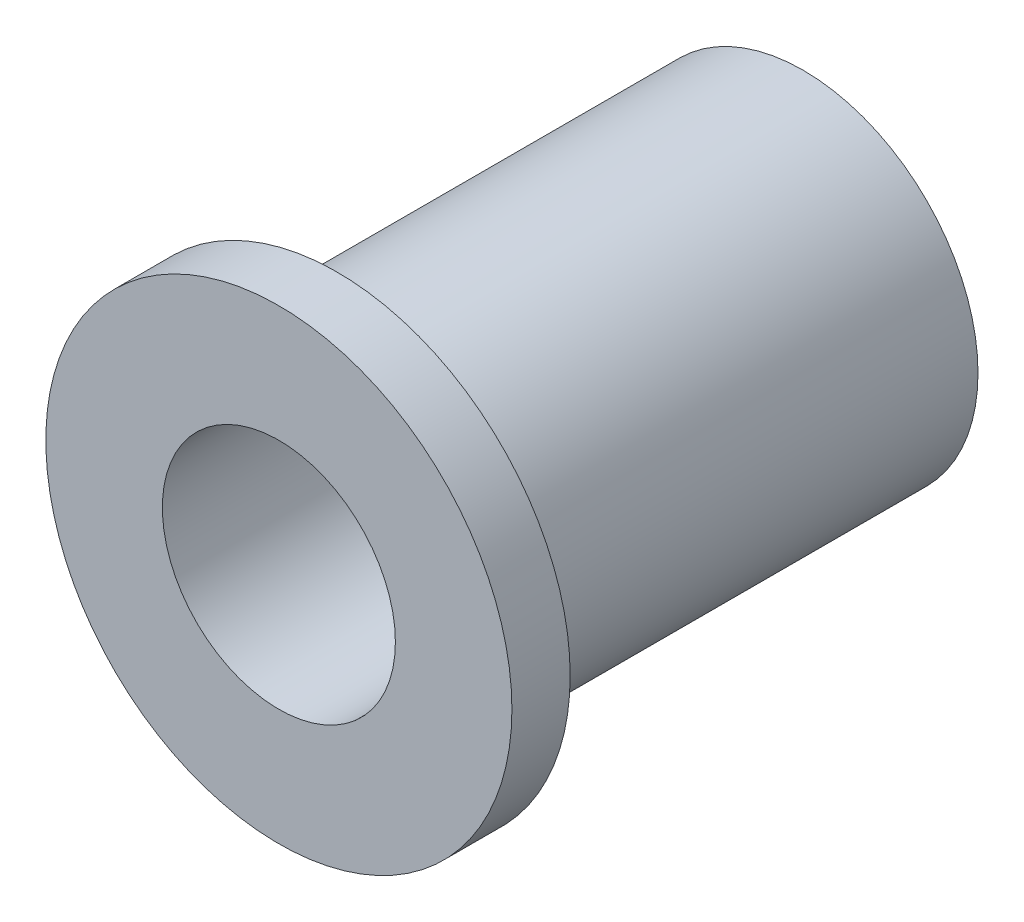
SolidWorks part; units mm, degrees
ref_plane "Front Plane" through (0, 0, 0) normal (0, 0, 1) x (1, 0, 0)
ref_plane "Top Plane" through (0, 0, 0) normal (0, 1, 0) x (1, 0, 0)
ref_plane "Right Plane" through (0, 0, 0) normal (1, 0, 0) x (0, 0, -1)
sketch "Sketch1" plane through (0, 0, 0) normal (0, 0, 1) x (1, 0, 0)
  circle A0 centre (0, 0) radius 9.525
  circle A1 centre (0, 0) radius 6.35
  dimension "D1" = 19.05
  dimension "D2" = 12.7
extrude "Boss-Extrude1" add sketch "Sketch1" along normal mid plane 25.4
sketch "Sketch2" plane through (0, 0, 12.7) normal (0, 0, 1) x (1, 0, 0)
  circle A0 centre (0, 0) radius 12.7
  circle A1 centre (0, 0) radius 6.35
  dimension "D1" = 25.4
  dimension "D2" = 12.7
extrude "Boss-Extrude2" add sketch "Sketch2" along normal blind 3.175
